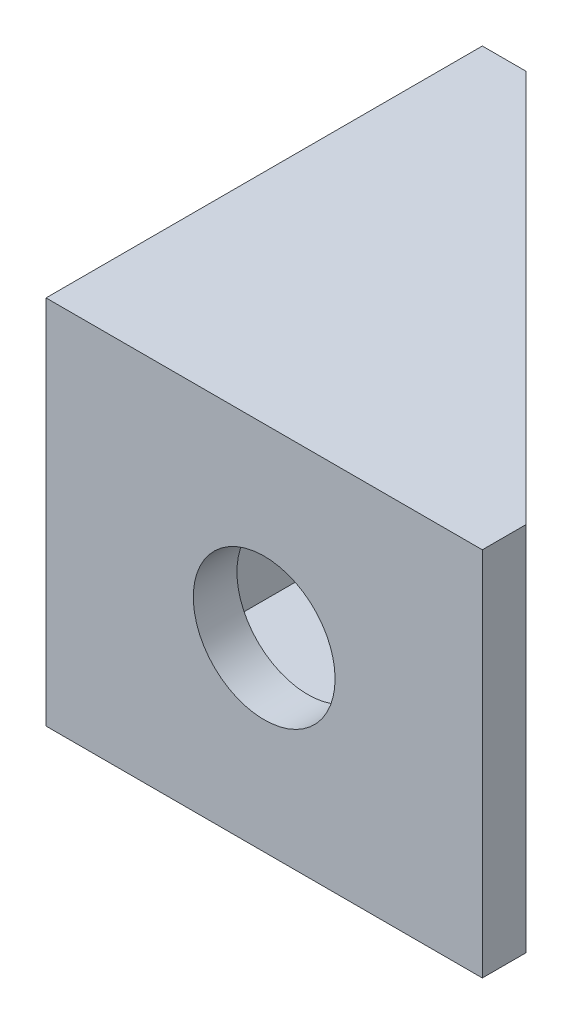
SolidWorks part; units mm, degrees
material "Cast Stainless Steel"
ref_plane "Front Plane" through (0, 0, 0) normal (0, 0, 1) x (1, 0, 0)
ref_plane "Top Plane" through (0, 0, 0) normal (0, 1, 0) x (1, 0, 0)
ref_plane "Right Plane" through (0, 0, 0) normal (1, 0, 0) x (0, 0, -1)
sketch "Sketch1" plane through (0, 0, 0) normal (0, 0, 1) x (1, 0, 0)
  line L0 (20, 0) -> (0, 17) construction
  line L1 (0, 0) -> (20, 0)
  line L2 (0, 0) -> (0, 17)
  line L3 (0, 17) -> (20, 17)
  line L4 (20, 0) -> (20, 17)
  circle A0 centre (10, 8.5) radius 3.25
  dimension "D3" = 6.5
  dimension "D1" = 20
  dimension "D2" = 17
sketch "Sketch2" plane through (0, 0, 0) normal (1, 0, 0) x (0, 0, -1)
  line L1 (0, 0) -> (20, 0)
  line L2 (0, 0) -> (0, 17)
  line L3 (0, 17) -> (20, 17)
  line L4 (20, 0) -> (20, 17)
  line L5 (20, 17) -> (0, 0) construction
  circle A0 centre (10, 8.5) radius 3.25
  dimension "D2" = 6.5
  dimension "D1" = 20
extrude "Boss-Extrude1" add sketch "Sketch1" against normal blind 2
extrude "Boss-Extrude2" add sketch "Sketch2" along normal blind 2
sketch "Sketch3" plane through (0, 17, 0) normal (0, 1, 0) x (1, 0, 0)
  line L0 (2, 20) -> (20, 2)
  line L1 (20, 2) -> (2, 2)
  line L2 (2, 2) -> (2, 20)
extrude "Boss-Extrude3" add sketch "Sketch3" against normal blind 2
sketch "Sketch4" plane through (0, 0, 0) normal (0, -1, 0) x (1, 0, 0)
  line L0 (2, -20) -> (20, -2)
  line L1 (20, -2) -> (2, -2)
  line L2 (2, -2) -> (2, -20)
extrude "Boss-Extrude4" add sketch "Sketch4" against normal blind 2
